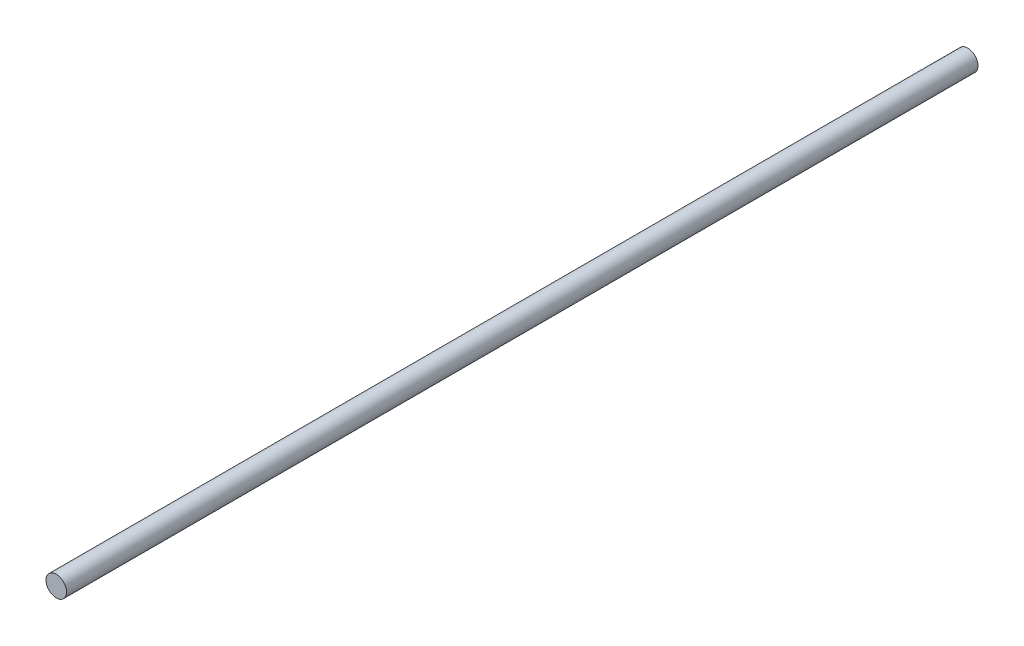
SolidWorks part; units mm, degrees
ref_plane "Front Plane" through (0, 0, 0) normal (0, 0, 1) x (1, 0, 0)
ref_plane "Top Plane" through (0, 0, 0) normal (0, 1, 0) x (1, 0, 0)
ref_plane "Right Plane" through (0, 0, 0) normal (1, 0, 0) x (0, 0, -1)
sketch "Sketch1" plane through (0, 0, 0) normal (0, 0, 1) x (1, 0, 0)
  circle A0 centre (0, 0) radius 1.5
  dimension "D1" = 3
extrude "Boss-Extrude1" add sketch "Sketch1" along normal blind 133
